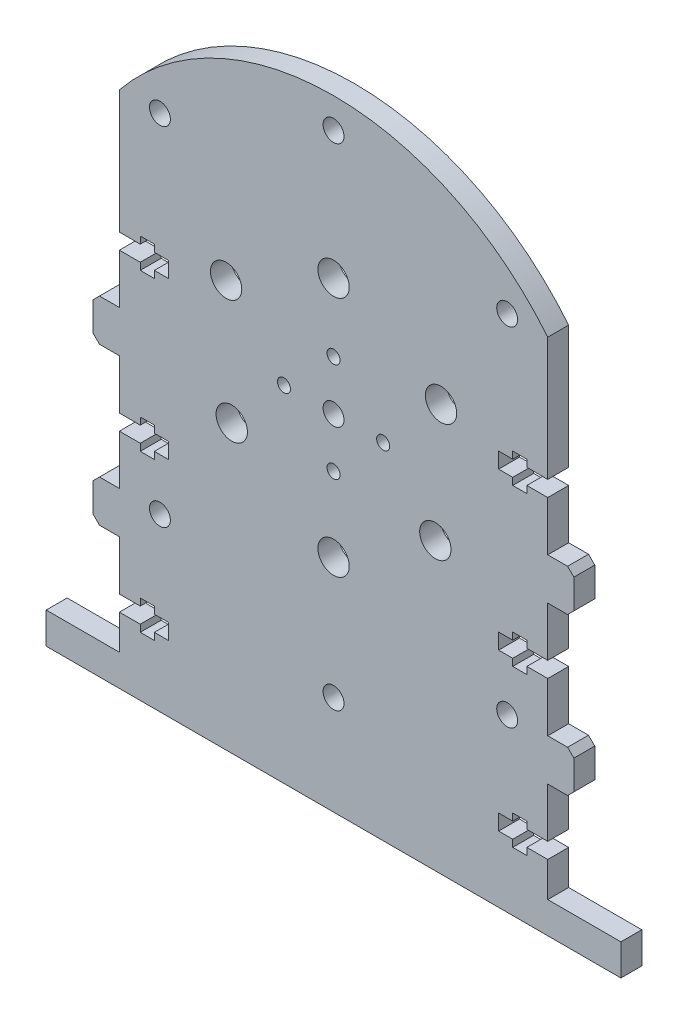
SolidWorks part; units mm, degrees
ref_plane "前视基准面" through (0, 0, 0) normal (0, 0, 1) x (1, 0, 0)
ref_plane "上视基准面" through (0, 0, 0) normal (0, 1, 0) x (1, 0, 0)
ref_plane "右视基准面" through (0, 0, 0) normal (1, 0, 0) x (0, 0, -1)
sketch "草图1" plane through (0, 0, 0) normal (0, 0, 1) x (1, 0, 0)
  line L0 (-14.9625, -1.5035) -> (21.2348, -1.5035) construction
  line L1 (-14.9625, -1.5035) -> (24.3099, -24.1774) construction
  line L2 (-14.9625, -25.2535) -> (-14.9625, -1.5035) construction
  line L3 (26.0375, -61.5035) -> (-55.9625, -61.5035)
  line L4 (26.0375, -61.5035) -> (26.0375, 58.4965) construction
  line L5 (26.0375, 58.4965) -> (-55.9625, 58.4965) construction
  line L7 (26.0375, -61.5035) -> (-55.9625, 58.4965) construction
  line L8 (26.0375, 58.4965) -> (-55.9625, -61.5035) construction
  line L9 (-14.9625, -1.5035) -> (-98.8628, 46.9364) construction
  line L10 (-14.9625, -1.5035) -> (68.9378, 46.9364) construction
  line L11 (-58.2638, 23.4965) -> (-55.9625, 23.4965) construction
  line L12 (-55.9625, 23.4965) -> (-55.9625, 8.1465)
  line L13 (-55.9625, 8.1465) -> (-51.9625, 8.1465)
  line L14 (-51.9625, 8.1465) -> (-51.9625, 9.4965)
  line L15 (-51.9625, 9.4965) -> (-49.2625, 9.4965)
  line L16 (-49.2625, 9.4965) -> (-49.2625, 8.1465)
  line L17 (-49.2625, 8.1465) -> (-46.5625, 8.1465)
  line L18 (-46.5625, 8.1465) -> (-46.5625, 5.1465)
  line L19 (-46.5625, 5.1465) -> (-49.2625, 5.1465)
  line L20 (-49.2625, 5.1465) -> (-49.2625, 3.7965)
  line L21 (-49.2625, 3.7965) -> (-51.9625, 3.7965)
  line L22 (-51.9625, 3.7965) -> (-51.9625, 5.1465)
  line L23 (-51.9625, 5.1465) -> (-55.9625, 5.1465)
  line L24 (-55.9625, -4.3535) -> (-60.9625, -4.3535)
  line L25 (-60.9625, -4.3535) -> (-60.9625, -12.3535)
  line L26 (-60.9625, -12.3535) -> (-55.9625, -12.3535)
  line L27 (-60.9625, -8.3535) -> (-58.1553, -8.3535) construction
  line L28 (-51.9625, -21.8535) -> (-55.9625, -21.8535)
  line L29 (-51.9625, -20.5035) -> (-51.9625, -21.8535)
  line L30 (-49.2625, -20.5035) -> (-51.9625, -20.5035)
  line L31 (-49.2625, -21.8535) -> (-49.2625, -20.5035)
  line L32 (-46.5625, -21.8535) -> (-49.2625, -21.8535)
  line L33 (-46.5625, -24.8535) -> (-46.5625, -21.8535)
  line L34 (-49.2625, -24.8535) -> (-46.5625, -24.8535)
  line L35 (-49.2625, -26.2035) -> (-49.2625, -24.8535)
  line L36 (-51.9625, -26.2035) -> (-49.2625, -26.2035)
  line L37 (-51.9625, -24.8535) -> (-51.9625, -26.2035)
  line L38 (-55.9625, -24.8535) -> (-51.9625, -24.8535)
  line L39 (-55.9625, -21.8535) -> (-55.9625, -12.3535)
  line L40 (-46.5625, -23.3535) -> (-48.2625, -23.3535) construction
  line L41 (-55.9625, -42.3535) -> (-60.9625, -42.3535)
  line L42 (-60.9625, -42.3535) -> (-60.9625, -34.3535)
  line L43 (-60.9625, -34.3535) -> (-55.9625, -34.3535)
  line L44 (-60.9625, -38.3535) -> (-57.1747, -38.3535) construction
  line L45 (-46.5625, -53.3535) -> (-48.2625, -53.3535) construction
  line L46 (-55.9625, 5.1465) -> (-55.9625, -4.3535)
  line L47 (-55.9625, -24.8535) -> (-55.9625, -34.3535)
  line L48 (-55.9625, -51.8535) -> (-51.9625, -51.8535)
  line L49 (-51.9625, -51.8535) -> (-51.9625, -50.5035)
  line L50 (-51.9625, -50.5035) -> (-49.2625, -50.5035)
  line L51 (-49.2625, -50.5035) -> (-49.2625, -51.8535)
  line L52 (-49.2625, -51.8535) -> (-46.5625, -51.8535)
  line L53 (-46.5625, -51.8535) -> (-46.5625, -54.8535)
  line L54 (-46.5625, -54.8535) -> (-49.2625, -54.8535)
  line L55 (-49.2625, -54.8535) -> (-49.2625, -56.2035)
  line L56 (-49.2625, -56.2035) -> (-51.9625, -56.2035)
  line L57 (-51.9625, -56.2035) -> (-51.9625, -54.8535)
  line L58 (-51.9625, -54.8535) -> (-55.9625, -54.8535)
  line L59 (-55.9625, -42.3535) -> (-55.9625, -51.8535)
  line L60 (-55.9625, -54.8535) -> (-55.9625, -61.5035)
  line L61 (16.6375, -53.3535) -> (18.3375, -53.3535) construction
  line L62 (31.0375, -38.3535) -> (27.2497, -38.3535) construction
  line L63 (16.6375, -23.3535) -> (18.3375, -23.3535) construction
  line L64 (31.0375, -8.3535) -> (28.2303, -8.3535) construction
  line L65 (26.0375, -42.3535) -> (26.0375, -51.8535)
  line L66 (22.0375, -54.8535) -> (26.0375, -54.8535)
  line L67 (22.0375, -56.2035) -> (22.0375, -54.8535)
  line L68 (19.3375, -56.2035) -> (22.0375, -56.2035)
  line L69 (19.3375, -54.8535) -> (19.3375, -56.2035)
  line L70 (16.6375, -54.8535) -> (19.3375, -54.8535)
  line L71 (16.6375, -51.8535) -> (16.6375, -54.8535)
  line L72 (19.3375, -51.8535) -> (16.6375, -51.8535)
  line L73 (19.3375, -50.5035) -> (19.3375, -51.8535)
  line L74 (22.0375, -50.5035) -> (19.3375, -50.5035)
  line L75 (22.0375, -51.8535) -> (22.0375, -50.5035)
  line L76 (26.0375, -51.8535) -> (22.0375, -51.8535)
  line L77 (26.0375, -24.8535) -> (26.0375, -34.3535)
  line L78 (26.0375, 5.1465) -> (26.0375, -4.3535)
  line L79 (31.0375, -34.3535) -> (26.0375, -34.3535)
  line L80 (31.0375, -42.3535) -> (31.0375, -34.3535)
  line L81 (26.0375, -42.3535) -> (31.0375, -42.3535)
  line L82 (26.0375, -21.8535) -> (26.0375, -12.3535)
  line L83 (26.0375, -24.8535) -> (22.0375, -24.8535)
  line L84 (22.0375, -24.8535) -> (22.0375, -26.2035)
  line L85 (22.0375, -26.2035) -> (19.3375, -26.2035)
  line L86 (19.3375, -26.2035) -> (19.3375, -24.8535)
  line L87 (19.3375, -24.8535) -> (16.6375, -24.8535)
  line L88 (16.6375, -24.8535) -> (16.6375, -21.8535)
  line L89 (16.6375, -21.8535) -> (19.3375, -21.8535)
  line L90 (19.3375, -21.8535) -> (19.3375, -20.5035)
  line L91 (19.3375, -20.5035) -> (22.0375, -20.5035)
  line L92 (22.0375, -20.5035) -> (22.0375, -21.8535)
  line L93 (22.0375, -21.8535) -> (26.0375, -21.8535)
  line L94 (31.0375, -12.3535) -> (26.0375, -12.3535)
  line L95 (31.0375, -4.3535) -> (31.0375, -12.3535)
  line L96 (26.0375, -4.3535) -> (31.0375, -4.3535)
  line L97 (22.0375, 5.1465) -> (26.0375, 5.1465)
  line L98 (22.0375, 3.7965) -> (22.0375, 5.1465)
  line L99 (19.3375, 3.7965) -> (22.0375, 3.7965)
  line L100 (19.3375, 5.1465) -> (19.3375, 3.7965)
  line L101 (16.6375, 5.1465) -> (19.3375, 5.1465)
  line L102 (16.6375, 8.1465) -> (16.6375, 5.1465)
  line L103 (19.3375, 8.1465) -> (16.6375, 8.1465)
  line L104 (19.3375, 9.4965) -> (19.3375, 8.1465)
  line L105 (22.0375, 9.4965) -> (19.3375, 9.4965)
  line L106 (22.0375, 8.1465) -> (22.0375, 9.4965)
  line L107 (26.0375, 8.1465) -> (22.0375, 8.1465)
  line L108 (26.0375, 23.4965) -> (26.0375, 8.1465)
  line L109 (28.3388, 23.4965) -> (26.0375, 23.4965) construction
  line L110 (26.0375, -54.8535) -> (26.0375, -61.5035)
  line L115 (-55.9625, 23.4965) -> (-55.9625, 31.723)
  line L116 (26.0375, 23.4965) -> (26.0375, 31.723)
  circle A0 centre (-14.9625, -1.5035) radius 23.75 construction
  circle A1 centre (-14.9625, -1.5035) radius 22.5 construction
  circle A2 centre (-14.9625, -25.2535) radius 3
  circle A5 centre (4.5231, -12.7535) radius 3
  circle A8 centre (-14.9625, -1.5035) radius 2
  circle A15 centre (-14.9625, -1.5035) radius 47 construction
  circle A17 centre (-35.5306, 10.3715) radius 3
  circle A18 centre (-34.4481, -12.7535) radius 3
  circle A19 centre (5.6056, 10.3715) radius 3
  circle A20 centre (-14.9625, 20.9965) radius 3
  circle A21 centre (32.0375, -1.5035) radius 2 construction
  circle A22 centre (18.2715, -34.7375) radius 2
  circle A23 centre (-14.9625, -48.5035) radius 2
  circle A24 centre (-48.1965, -34.7375) radius 2
  circle A25 centre (-61.9625, -1.5035) radius 2 construction
  circle A26 centre (-48.1965, 31.7305) radius 2
  circle A27 centre (-14.9625, 45.4965) radius 2
  circle A28 centre (18.2715, 31.7305) radius 2
  circle A31 centre (-14.9625, -1.5035) radius 52.7731 construction
  arc A34 (-55.9625, 31.723) -> (26.0375, 31.723) centre (-14.9625, -1.5035) cw
  circle A35 centre (-14.9625, -1.5035) radius 9.5 construction
  circle A36 centre (-14.9625, 7.9965) radius 1.25
  circle A37 centre (-5.4625, -1.5035) radius 1.25
  circle A38 centre (-14.9625, -11.0035) radius 1.25
  circle A39 centre (-24.4625, -1.5035) radius 1.25
  point P41 (-54.9625, -8.3535)
  point P135 (25.0375, -8.3535)
  dimension "D1" = 47.5
  dimension "D2" = 45
  dimension "D3" = 6
  dimension "D5" = 6
  dimension "D18" = 60
  dimension "D19" = 8
  dimension "D20" = 4
  dimension "D21" = 94
  dimension "D22" = 19
  dimension "D23" = 4
  dimension "D24" = 2.5
  dimension "D4" = 30
  dimension "D6" = 82
  dimension "D8" = 120
  dimension "D9" = 3
  dimension "D10" = 2.7
  dimension "D11" = 5.7
  dimension "D12" = 4
  dimension "D13" = 14
  dimension "D14" = 13.5
  dimension "D15" = 8
  dimension "D16" = 5
  dimension "D17" = 4
  dimension "D7" = 3
extrude "凸台-拉伸2" add sketch "草图1" along normal blind 4
sketch "草图2" plane through (-55.9625, 0, 0) normal (-1, 0, 0) x (0, 0, 1)
  line L0 (2, -54.8535) -> (2, -51.8535)
  line L1 (4, -54.8535) -> (0, -54.8535) construction
  line L2 (4, -51.8535) -> (0, -51.8535) construction
  circle A0 centre (2, -53.3535) radius 1.5
sketch "草图3" plane through (26.0375, 0, 0) normal (1, 0, 0) x (0, 0, -1)
  line L0 (-2, -51.8535) -> (-2, -54.8535)
  line L1 (-4, -51.8535) -> (0, -51.8535) construction
  line L2 (-4, -54.8535) -> (0, -54.8535) construction
  circle A0 centre (-2, -53.3535) radius 1.5
sketch "草图4" plane through (0, 0, 4) normal (0, 0, 1) x (1, 0, 0)
  line L0 (26.0375, -61.5035) -> (26.0375, -54.8535) construction
  line L1 (-69.9625, -61.5035) -> (40.0375, -61.5035)
  line L2 (-69.9625, -61.5035) -> (-69.9625, -67.5035)
  line L3 (-69.9625, -67.5035) -> (40.0375, -67.5035)
  line L4 (40.0375, -61.5035) -> (40.0375, -67.5035)
  line L5 (-55.9625, -54.8535) -> (-55.9625, -61.5035) construction
  line L6 (-55.9625, -61.5035) -> (26.0375, -61.5035) construction
  dimension "D1" = 14
  dimension "D2" = 14
  dimension "D3" = 6
extrude "凸台-拉伸3" add sketch "草图4" against normal blind 4
sketch "草图5" plane through (0, 0, 4) normal (0, 0, 1) x (1, 0, 0)
  line L0 (-60.9625, -4.3535) -> (-59.7625, -4.3535)
  line L1 (-55.9625, -4.3535) -> (-60.9625, -4.3535) construction
  line L2 (-59.7625, -4.3535) -> (-60.9625, -5.5535)
  line L3 (-60.9625, -4.3535) -> (-60.9625, -12.3535) construction
  line L4 (-60.9625, -5.5535) -> (-60.9625, -4.3535)
  line L5 (-60.9625, -12.3535) -> (-59.7625, -12.3535)
  line L6 (-60.9625, -12.3535) -> (-55.9625, -12.3535) construction
  line L7 (-59.7625, -12.3535) -> (-60.9625, -11.1535)
  line L8 (-60.9625, -11.1535) -> (-60.9625, -12.3535)
  line L9 (-60.9625, -34.3535) -> (-59.7625, -34.3535)
  line L10 (-55.9625, -34.3535) -> (-60.9625, -34.3535) construction
  line L11 (-59.7625, -34.3535) -> (-60.9625, -35.5535)
  line L12 (-60.9625, -34.3535) -> (-60.9625, -42.3535) construction
  line L13 (-60.9625, -35.5535) -> (-60.9625, -34.3535)
  line L14 (-60.9625, -42.3535) -> (-59.7625, -42.3535)
  line L15 (-60.9625, -42.3535) -> (-55.9625, -42.3535) construction
  line L16 (-59.7625, -42.3535) -> (-60.9625, -41.1535)
  line L17 (-60.9625, -41.1535) -> (-60.9625, -42.3535)
  line L18 (31.0375, -42.3535) -> (31.0375, -41.1535)
  line L19 (31.0375, -42.3535) -> (31.0375, -34.3535) construction
  line L20 (31.0375, -41.1535) -> (29.8375, -42.3535)
  line L21 (26.0375, -42.3535) -> (31.0375, -42.3535) construction
  line L22 (29.8375, -42.3535) -> (31.0375, -42.3535)
  line L23 (29.8375, -34.3535) -> (31.0375, -34.3535)
  line L24 (31.0375, -34.3535) -> (26.0375, -34.3535) construction
  line L25 (31.0375, -34.3535) -> (31.0375, -35.5535)
  line L26 (31.0375, -35.5535) -> (29.8375, -34.3535)
  line L27 (31.0375, -12.3535) -> (29.8375, -12.3535)
  line L28 (26.0375, -12.3535) -> (31.0375, -12.3535) construction
  line L29 (29.8375, -12.3535) -> (31.0375, -11.1535)
  line L30 (31.0375, -12.3535) -> (31.0375, -4.3535) construction
  line L31 (31.0375, -11.1535) -> (31.0375, -12.3535)
  line L32 (31.0375, -4.3535) -> (29.8375, -4.3535)
  line L33 (31.0375, -4.3535) -> (26.0375, -4.3535) construction
  line L34 (29.8375, -4.3535) -> (31.0375, -5.5535)
  line L35 (31.0375, -5.5535) -> (31.0375, -4.3535)
  dimension "D1" = 1.2
extrude "切除-拉伸1" cut sketch "草图5" against normal blind 4
